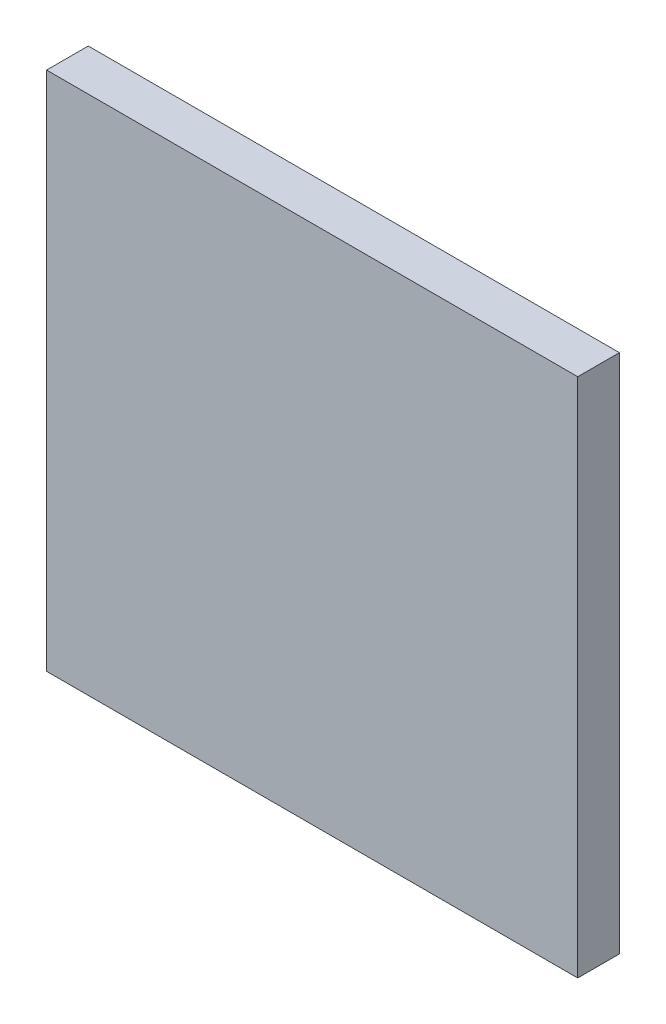
SolidWorks part; units mm, degrees
ref_plane "Front Plane" through (0, 0, 0) normal (0, 0, 1) x (1, 0, 0)
ref_plane "Top Plane" through (0, 0, 0) normal (0, 1, 0) x (1, 0, 0)
ref_plane "Right Plane" through (0, 0, 0) normal (1, 0, 0) x (0, 0, -1)
sketch "Sketch1" plane through (0, 0, 0) normal (0, 0, 1) x (1, 0, 0)
  line L1 (-127.5, -125) -> (127.5, -125)
  line L2 (-127.5, -125) -> (-127.5, 125)
  line L3 (-127.5, 125) -> (127.5, 125)
  line L4 (127.5, -125) -> (127.5, 125)
  line L5 (-127.5, -125) -> (127.5, 125) construction
  line L6 (-127.5, 125) -> (127.5, -125) construction
  point P0 (0, 0)
  dimension "D1" = 250
  dimension "D2" = 255
extrude "Boss-Extrude1" add sketch "Sketch1" along normal blind 20
